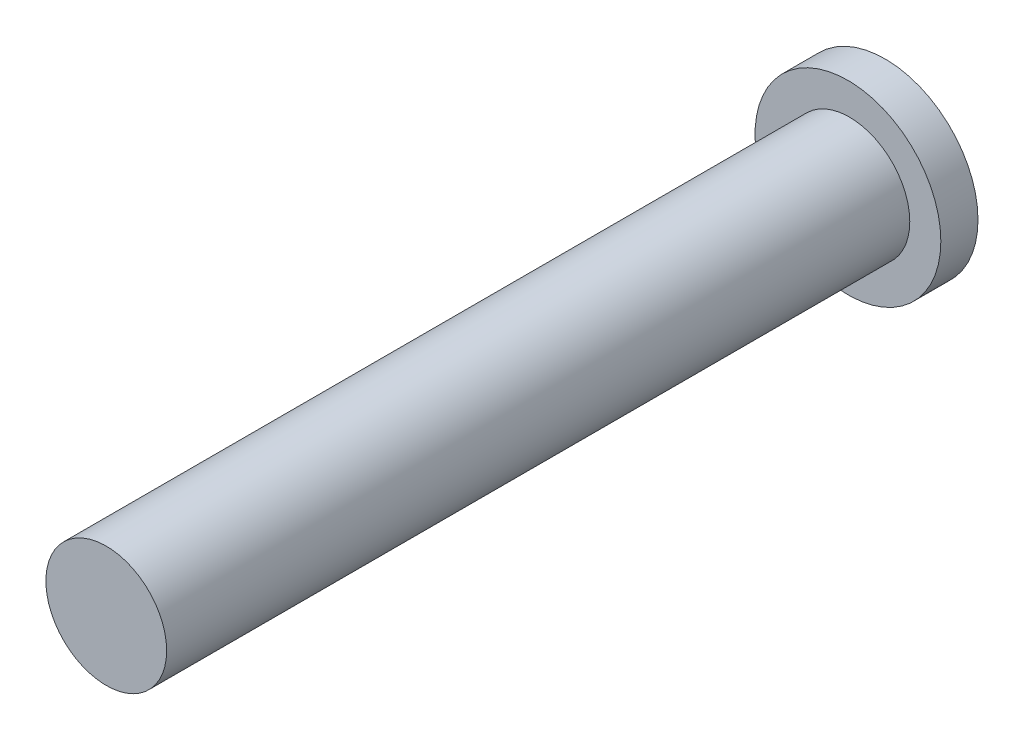
SolidWorks part; units mm, degrees
material "1023 Carbon Steel Sheet (SS)"
ref_plane "Front Plane" through (0, 0, 0) normal (0, 0, 1) x (1, 0, 0)
ref_plane "Top Plane" through (0, 0, 0) normal (0, 1, 0) x (1, 0, 0)
ref_plane "Right Plane" through (0, 0, 0) normal (1, 0, 0) x (0, 0, -1)
sketch "Sketch2" plane through (0, 0, 0) normal (0, 0, 1) x (1, 0, 0)
  circle A0 centre (-2.4657, 0.4035) radius 5
  dimension "D1" = 10
extrude "Boss-Extrude1" add sketch "Sketch2" along normal blind 2
sketch "Sketch3" plane through (0, 0, 2) normal (0, 0, 1) x (1, 0, 0)
  circle A0 centre (-2.3876, 0.4816) radius 3.25
extrude "Boss-Extrude2" add sketch "Sketch3" along normal blind 40
